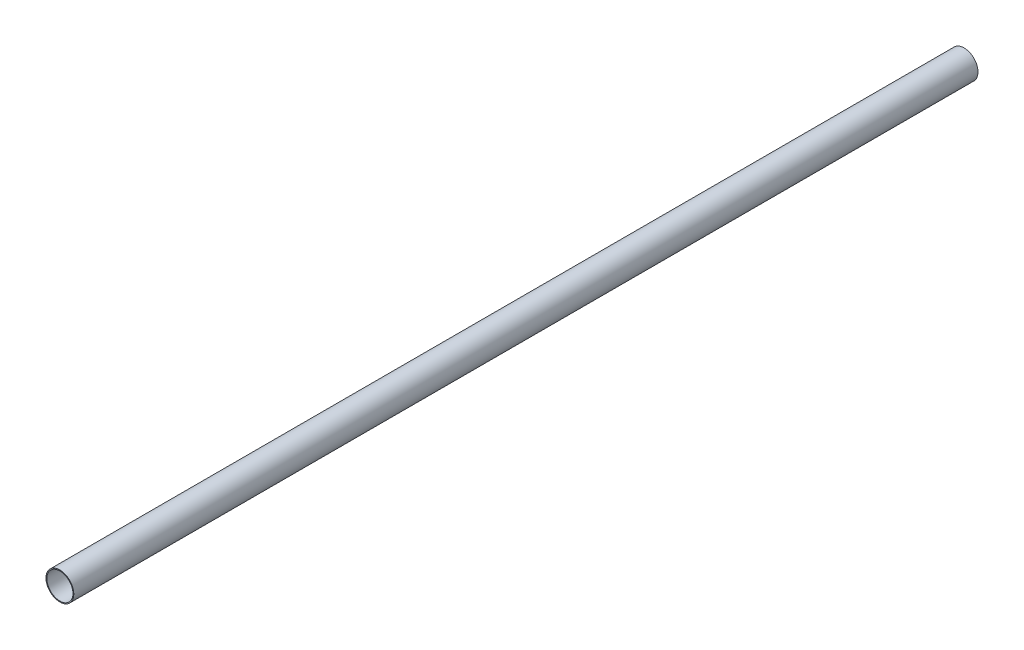
SolidWorks part; units mm, degrees
material "NEOPRENE"
ref_plane "Front Plane" through (0, 0, 0) normal (0, 0, 1) x (1, 0, 0)
ref_plane "Top Plane" through (0, 0, 0) normal (0, 1, 0) x (1, 0, 0)
ref_plane "Right Plane" through (0, 0, 0) normal (1, 0, 0) x (0, 0, -1)
sketch "Sketch1" plane through (0, 0, 0) normal (0, 0, 1) x (1, 0, 0)
  circle A0 centre (0, 0) radius 3.75
  circle A1 centre (0, 0) radius 4
  dimension "D1" = 8
  dimension "D2" = 7.5
sketch "Sketch2" plane through (0, 0, 0) normal (1, 0, 0) x (0, 0, -1)
  line L0 (0, 0) -> (260, 0)
  dimension "D1" = 260
sweep "Sweep1" add profiles "Sketch1" path "Sketch2"
